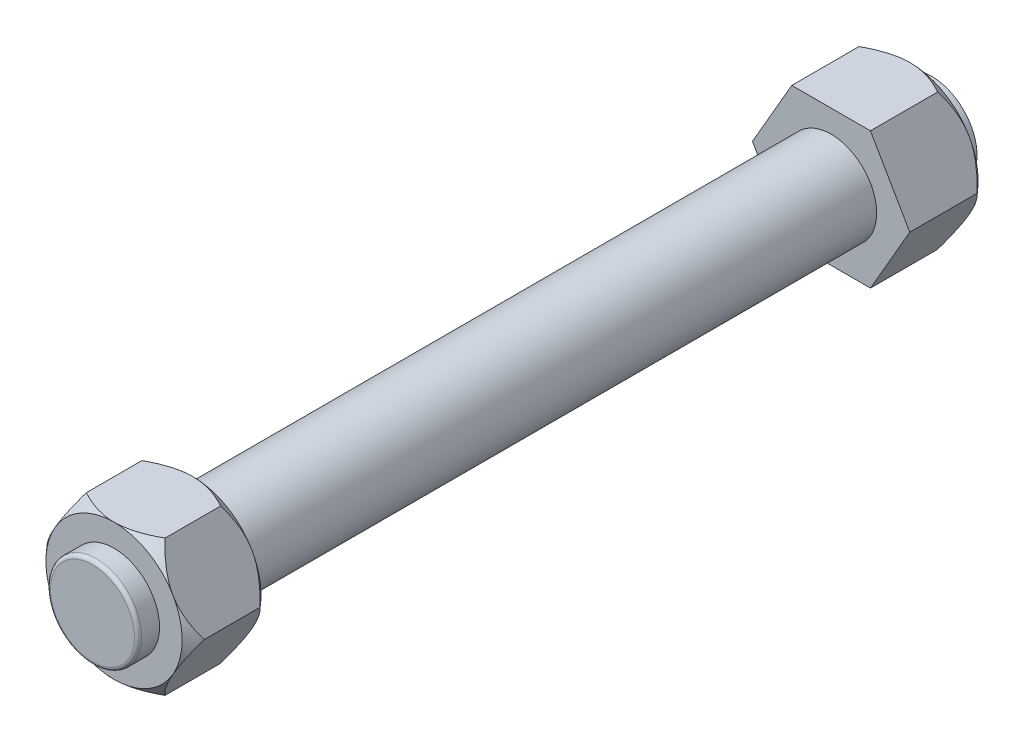
SolidWorks part; units mm, degrees
ref_plane "Alzado" through (0, 0, 0) normal (0, 0, 1) x (1, 0, 0)
ref_plane "Planta" through (0, 0, 0) normal (0, 1, 0) x (1, 0, 0)
ref_plane "Vista lateral" through (0, 0, 0) normal (1, 0, 0) x (0, 0, -1)
sketch "Croquis1" plane through (0, 0, 0) normal (0, 0, 1) x (1, 0, 0)
  circle A0 centre (0, 0) radius 6.35
  dimension "D1" = 12.7
extrude "Saliente-Extruir1" add sketch "Croquis1" against normal blind 117
sketch "Croquis2" plane through (0, 0, 0) normal (0, 0, 1) x (1, 0, 0)
  line L1 (10.9697, 0) -> (5.4848, 9.5)
  line L2 (5.4848, 9.5) -> (-5.4848, 9.5)
  line L3 (-5.4848, 9.5) -> (-10.9697, 0)
  line L4 (-10.9697, 0) -> (-5.4848, -9.5)
  line L5 (-5.4848, -9.5) -> (5.4848, -9.5)
  line L6 (5.4848, -9.5) -> (10.9697, 0)
  circle A0 centre (0, 0) radius 9.5 construction
  circle A1 centre (0, 0) radius 6.35
  dimension "D1" = 19
extrude "Saliente-Extruir2" add sketch "Croquis2" against normal blind 14
sketch "Croquis3" plane through (0, 0, 0) normal (0, 0, 1) x (1, 0, 0)
  line L1 (10.9697, 0) -> (5.4848, 9.5)
  line L2 (5.4848, 9.5) -> (-5.4848, 9.5)
  line L3 (-5.4848, 9.5) -> (-10.9697, 0)
  line L4 (-10.9697, 0) -> (-5.4848, -9.5)
  line L5 (-5.4848, -9.5) -> (5.4848, -9.5)
  line L6 (5.4848, -9.5) -> (10.9697, 0)
  circle A0 centre (0, 0) radius 6.35
  circle A1 centre (0, 0) radius 9.5 construction
extrude "Cortar-Extruir1" cut sketch "Croquis3" against normal blind 3
sketch "Croquis4" plane through (0, 0, -3) normal (0, 0, 1) x (1, 0, 0)
  circle A0 centre (0, 0) radius 9.5
  circle A1 centre (0, 0) radius 25.6447
extrude "Cortar-Extruir2" cut sketch "Croquis4" against normal blind 10 draft 42
sketch "Croquis5" plane through (0, 0, -14) normal (0, 0, -1) x (-1, 0, 0)
  circle A0 centre (0, 0) radius 9.5
  circle A1 centre (0, 0) radius 21.393
extrude "Cortar-Extruir3" cut sketch "Croquis5" against normal blind 10 draft 42
sketch "Croquis6" plane through (0, 0, -117) normal (0, 0, -1) x (-1, 0, 0)
  line L1 (10.9697, 0) -> (5.4848, 9.5)
  line L2 (5.4848, 9.5) -> (-5.4848, 9.5)
  line L3 (-5.4848, 9.5) -> (-10.9697, 0)
  line L4 (-10.9697, 0) -> (-5.4848, -9.5)
  line L5 (-5.4848, -9.5) -> (5.4848, -9.5)
  line L6 (5.4848, -9.5) -> (10.9697, 0)
  circle A0 centre (0, 0) radius 9.5 construction
extrude "Saliente-Extruir3" add sketch "Croquis6" against normal blind 14
sketch "Croquis7" plane through (0, 0, -117) normal (0, 0, -1) x (-1, 0, 0)
  line L1 (10.9697, 0) -> (5.4848, 9.5)
  line L2 (5.4848, 9.5) -> (-5.4848, 9.5)
  line L3 (-5.4848, 9.5) -> (-10.9697, 0)
  line L4 (-10.9697, 0) -> (-5.4848, -9.5)
  line L5 (-5.4848, -9.5) -> (5.4848, -9.5)
  line L6 (5.4848, -9.5) -> (10.9697, 0)
  circle A0 centre (0, 0) radius 6.35
  circle A1 centre (0, 0) radius 9.5 construction
extrude "Cortar-Extruir4" cut sketch "Croquis7" against normal blind 3
sketch "Croquis9" plane through (0, 0, -114) normal (0, 0, -1) x (-1, 0, 0)
  circle A0 centre (0, 0) radius 9.5
  circle A1 centre (0, 0) radius 21.1761
extrude "Cortar-Extruir5" cut sketch "Croquis9" against normal blind 3 draft 42
fillet "Redondeo1" radius 0.5 1 edges at (6.35, 0, 0)
